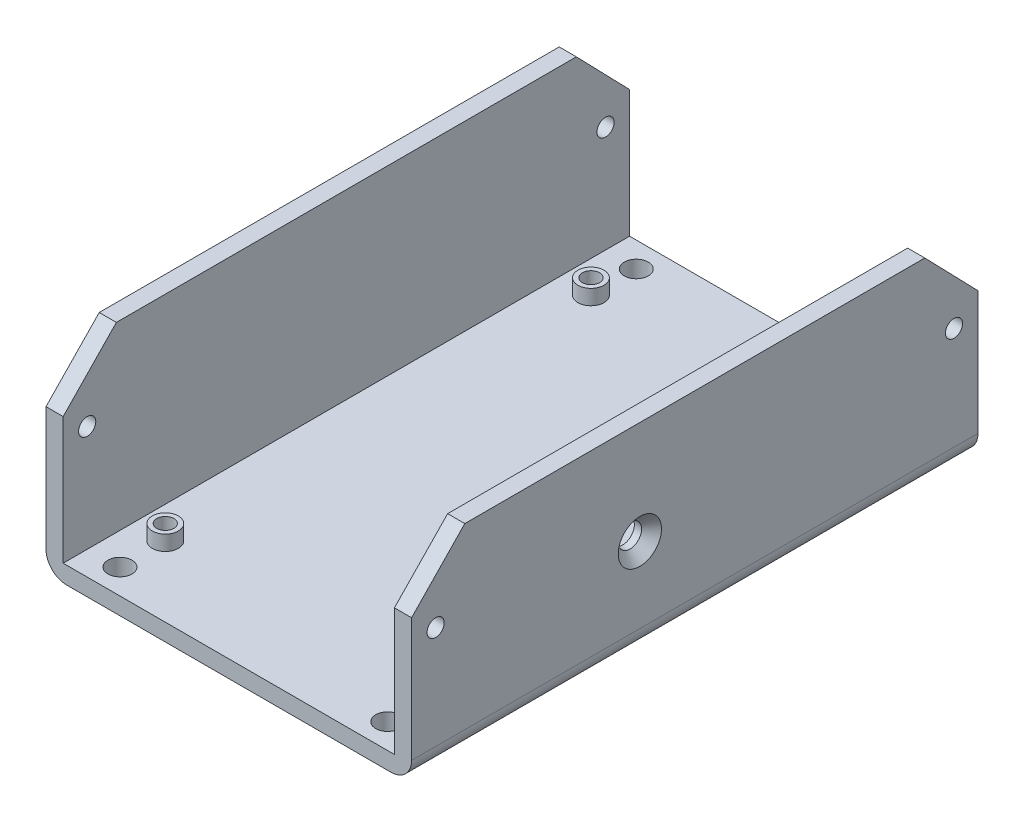
SolidWorks part; units mm, degrees
ref_plane "Спереди" through (0, 0, 0) normal (0, 0, 1) x (1, 0, 0)
ref_plane "Сверху" through (0, 0, 0) normal (0, 1, 0) x (1, 0, 0)
ref_plane "Справа" through (0, 0, 0) normal (1, 0, 0) x (0, 0, -1)
sketch "Эскиз1" plane through (0, 0, 0) normal (0, 0, 1) x (1, 0, 0)
  line L0 (-26.625, 29) -> (-26.625, 3)
  line L1 (-23.625, 0) -> (23.625, 0)
  line L2 (26.625, 3) -> (26.625, 29)
  line L3 (26.625, 29) -> (24.125, 29)
  line L4 (24.125, 29) -> (24.125, 2.5)
  line L5 (24.125, 2.5) -> (-24.125, 2.5)
  line L6 (-24.125, 2.5) -> (-24.125, 29)
  line L7 (-24.125, 29) -> (-26.625, 29)
  arc A0 (23.625, 0) -> (26.625, 3) centre (23.625, 3) ccw
  arc A1 (-26.625, 3) -> (-23.625, 0) centre (-23.625, 3) ccw
  point P12 (26.625, 0)
  point P15 (-26.625, 0)
  dimension "D5" = 3
  dimension "D1" = 53.25
  dimension "D2" = 2.5
  dimension "D3" = 2.5
  dimension "D4" = 29
extrude "Бобышка-Вытянуть1" add sketch "Эскиз1" along normal mid plane 82.5
sketch "Эскиз3" plane through (0, 0, 0) normal (1, 0, 0) x (0, 0, -1)
  line L0 (41.25, 3) -> (41.25, 29) construction
  line L1 (-41.25, 3) -> (-41.25, 29) construction
  line L2 (-41.25, 29) -> (41.25, 29) construction
  line L3 (41.25, 21) -> (41.25, 29)
  line L4 (-41.25, 21) -> (-41.25, 29)
  line L5 (-41.25, 29) -> (-33.5, 29)
  line L6 (-41.25, 21) -> (-33.5, 29)
  line L7 (33.5, 29) -> (41.25, 21)
  line L8 (33.5, 29) -> (41.25, 29)
  line L9 (-33.5, 29) -> (33.5, 29) construction
  line L10 (-41.25, 0) -> (41.25, 0) construction
  point P8 (0, 29)
  dimension "D1" = 67
  dimension "D2" = 21
extrude "Вырез-Вытянуть1" cut sketch "Эскиз3" against normal through all and the other way through all
sketch "Эскиз4" plane through (0, 0, 0) normal (0, -1, 0) x (1, 0, 0)
  line L1 (19.5, -37.6) -> (-19.5, -37.6) construction
  line L2 (19.5, -37.6) -> (19.5, 37.6) construction
  line L3 (19.5, 37.6) -> (-19.5, 37.6) construction
  line L4 (-19.5, -37.6) -> (-19.5, 37.6) construction
  line L5 (19.5, -37.6) -> (-19.5, 37.6) construction
  line L6 (19.5, 37.6) -> (-19.5, -37.6) construction
  circle A0 centre (-19.5, -37.6) radius 1.75
  circle A1 centre (-19.5, 37.6) radius 1.75
  circle A2 centre (19.5, 37.6) radius 1.75
  circle A3 centre (19.5, -37.6) radius 1.75
  point P0 (0, 0)
  dimension "D1" = 3.5
  dimension "D2" = 75.2
  dimension "D3" = 39
extrude "Вырез-Вытянуть2" cut sketch "Эскиз4" against normal blind 10
hole_wizard "Отверстие обработанное метчиком M31" positions "Эскиз5" profile "Эскиз6" tap size "M3" standard "DIN"
sketch "Эскиз5" plane through (26.625, 0, 0) normal (1, 0, 0) x (0, 0, -1)
  line L0 (37.75, 18) -> (-37.75, 18) construction
  line L2 (-33.5, 29) -> (33.5, 29) construction
  point P0 (37.75, 18)
  point P2 (-37.75, 18)
  point P9 (0, 18)
  dimension "D1" = 75.5
  dimension "D2" = 11
cosmetic thread "Отверстие резьбы1"
cosmetic thread "Отверстие резьбы2"
sketch "Эскиз6" plane through (26.625, 18, -37.75) normal (0, 1, 0) x (0, 0, -1)
  line L0 (0, 0) -> (0, 3.2501)
  line L1 (0, 3.2501) -> (1.25, 2.499)
  line L2 (1.25, 2.499) -> (1.25, 0)
  line L5 (1.25, 0) -> (0, 0)
  line L10 (0, 3.2501) -> (-1.25, 2.499) construction
  line L11 (0, -6.35) -> (0, 107.95) construction
  dimension "Диаметр сверла" = 2.5
  dimension "Глубина сверла" = 2.499
  dimension "Угол заточки сверла" = 118
hole_wizard "Отверстие обработанное метчиком M32" positions "Эскиз8" profile "Эскиз9" tap size "M3" standard "DIN"
sketch "Эскиз8" plane through (-26.625, 0, 0) normal (-1, 0, 0) x (0, 0, 1)
  point P0 (-37.75, 18)
  point P3 (37.75, 18)
sketch "Эскиз9" plane through (-26.625, 18, -37.75) normal (0, 1, 0) x (0, 0, 1)
  line L0 (0, 0) -> (0, 3.2501)
  line L1 (0, 3.2501) -> (1.25, 2.499)
  line L2 (1.25, 2.499) -> (1.25, 0)
  line L5 (1.25, 0) -> (0, 0)
  line L10 (0, 3.2501) -> (-1.25, 2.499) construction
  line L11 (0, -6.35) -> (0, 107.95) construction
  dimension "Диаметр сверла" = 2.5
  dimension "Глубина сверла" = 2.499
  dimension "Угол заточки сверла" = 118
cosmetic thread "Отверстие резьбы3"
cosmetic thread "Отверстие резьбы4"
sketch "Эскиз10" plane through (0, 2.5, 0) normal (0, 1, 0) x (1, 0, 0)
  line L1 (-19.5, 31) -> (19.5, 31) construction
  line L2 (-19.5, 31) -> (-19.5, -31) construction
  line L3 (-19.5, -31) -> (19.5, -31) construction
  line L4 (19.5, 31) -> (19.5, -31) construction
  line L5 (-19.5, 31) -> (19.5, -31) construction
  line L6 (-19.5, -31) -> (19.5, 31) construction
  circle A0 centre (19.5, 31) radius 1.9
  circle A1 centre (19.5, -31) radius 1.9
  circle A2 centre (-19.5, -31) radius 1.9
  circle A3 centre (-19.5, 31) radius 1.9
  point P0 (0, 0)
  dimension "D1" = 3.8
  dimension "D2" = 62
  dimension "D3" = 39
extrude "Бобышка-Вытянуть2" add sketch "Эскиз10" along normal blind 2.2
hole_wizard "Отверстие обработанное метчиком M33" positions "Эскиз11" profile "Эскиз12" tap size "M3" standard "DIN" end condition through all
sketch "Эскиз11" plane through (0, 4.7, 0) normal (0, 1, 0) x (1, 0, 0)
  point P0 (19.5, 31)
  point P3 (-19.5, 31)
  point P6 (19.5, -31)
  point P9 (-19.5, -31)
sketch "Эскиз12" plane through (19.5, 4.7, -31) normal (1, 0, 0) x (0, 0, 1)
  line L0 (0, 0) -> (0, 4.7)
  line L1 (0, 4.7) -> (1.25, 4.7)
  line L2 (1.25, 4.7) -> (1.25, 0)
  line L5 (1.25, 0) -> (0, 0)
  line L11 (0, -6.35) -> (0, 107.95) construction
  dimension "Диаметр проходного сверла" = 2.5
  dimension "Глубина проходного сверла" = 4.7
cosmetic thread "Отверстие резьбы5"
cosmetic thread "Отверстие резьбы6"
cosmetic thread "Отверстие резьбы7"
cosmetic thread "Отверстие резьбы8"
hole_wizard "Зенковка для винта с полупотайной головкой M31" positions "Эскиз13" profile "Эскиз15" countersink size "M3" standard "DIN"
sketch "Эскиз13" plane through (26.625, 0, 0) normal (1, 0, 0) x (0, 0, -1)
  point P0 (-8, 14)
sketch "Эскиз15" plane through (26.625, 14, 8) normal (0, 1, 0) x (0, 0, -1)
  line L0 (0, 0) -> (0, 9.5215)
  line L1 (0, 9.5215) -> (1.7, 8.5)
  line L2 (1.7, 8.5) -> (1.7, 1.45)
  line L3 (1.7, 1.45) -> (3.15, 0)
  line L5 (3.15, 0) -> (0, 0)
  line L6 (-1.7, 1.45) -> (-3.15, 0) construction
  line L10 (0, 9.5215) -> (-1.7, 8.5) construction
  line L11 (0, -6.35) -> (0, 107.95) construction
  dimension "Диаметр отверстия" = 3.4
  dimension "Глубина отверстия" = 8.5
  dimension "Диаметр передней зенковки" = 6.3
  dimension "Угол передней зенковки" = 90
  dimension "Угол заточки сверла" = 118
